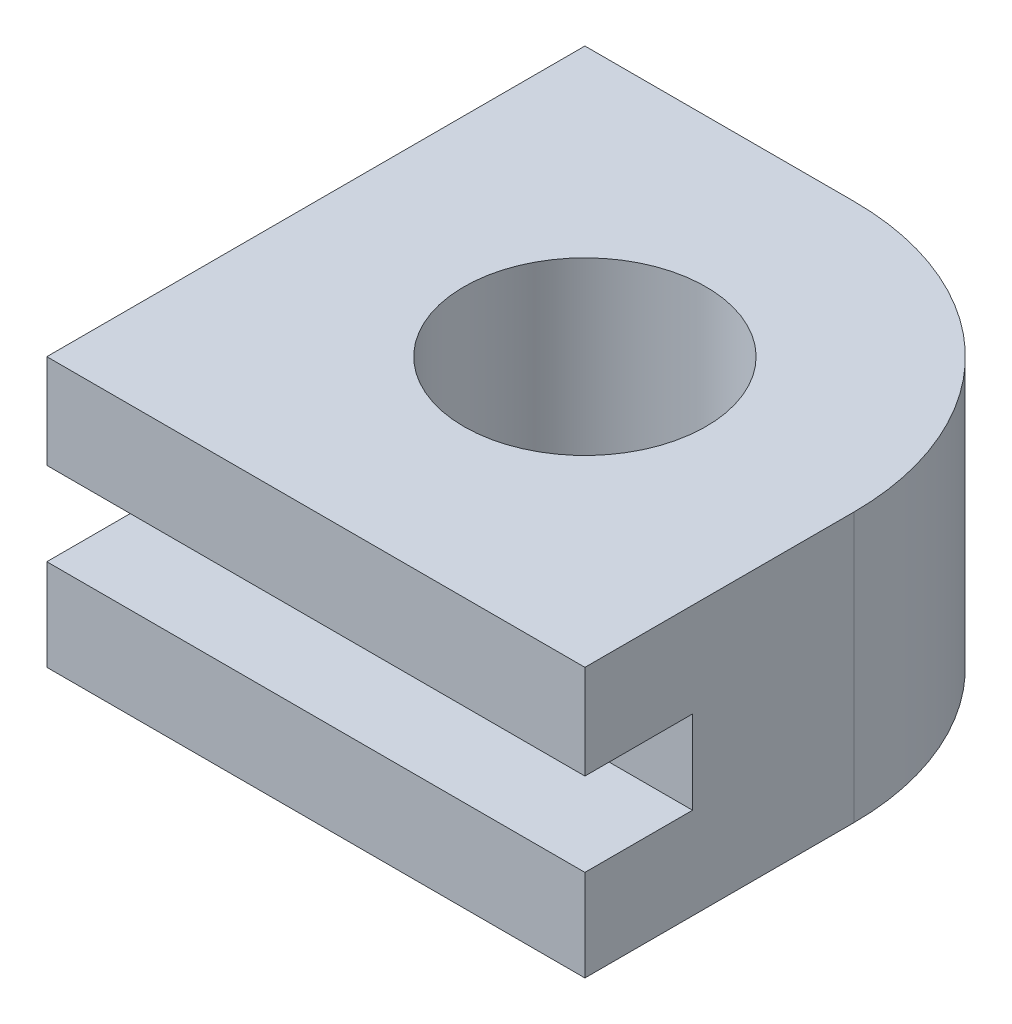
SolidWorks part; units mm, degrees
ref_plane "Front Plane" through (0, 0, 0) normal (0, 0, 1) x (1, 0, 0)
ref_plane "Top Plane" through (0, 0, 0) normal (0, 1, 0) x (1, 0, 0)
ref_plane "Right Plane" through (0, 0, 0) normal (1, 0, 0) x (0, 0, -1)
sketch "Sketch1" plane through (0, 0, 0) normal (0, 1, 0) x (1, 0, 0)
  line L1 (5, 5) -> (-5, 5)
  line L2 (5, 5) -> (5, -5)
  line L3 (5, -5) -> (-5, -5)
  line L4 (-5, 5) -> (-5, -5)
  line L5 (5, 5) -> (-5, -5) construction
  line L6 (5, -5) -> (-5, 5) construction
  circle A0 centre (0, 0) radius 2.25
  dimension "D1" = 4.5
  dimension "D2" = 10
extrude "Boss-Extrude1" add sketch "Sketch1" along normal blind 5
sketch "Sketch2" plane through (0, 5, 0) normal (0, 1, 0) x (1, 0, 0)
  line L1 (-3, 5) -> (-5, 5)
  line L2 (5, -3) -> (5, -5)
  line L3 (5, -5) -> (-5, -5)
  line L4 (-5, 5) -> (-5, -5)
  line L5 (5, 5) -> (-5, -5) construction
  line L6 (5, -5) -> (-5, 5) construction
  line L9 (5, -3) -> (-3, -3)
  line L10 (-3, 5) -> (-3, -3)
  line L11 (3, 3) -> (-3, -3) construction
  point P0 (0, 0)
  point P7 (0, 0)
  dimension "D1" = 3
extrude "Cut-Extrude1" cut sketch "Sketch2" against normal blind 1.55 from offset 1.75 offset against normal yes
fillet "Fillet1" radius 5 1 edges at (5, 2.5, -5)
